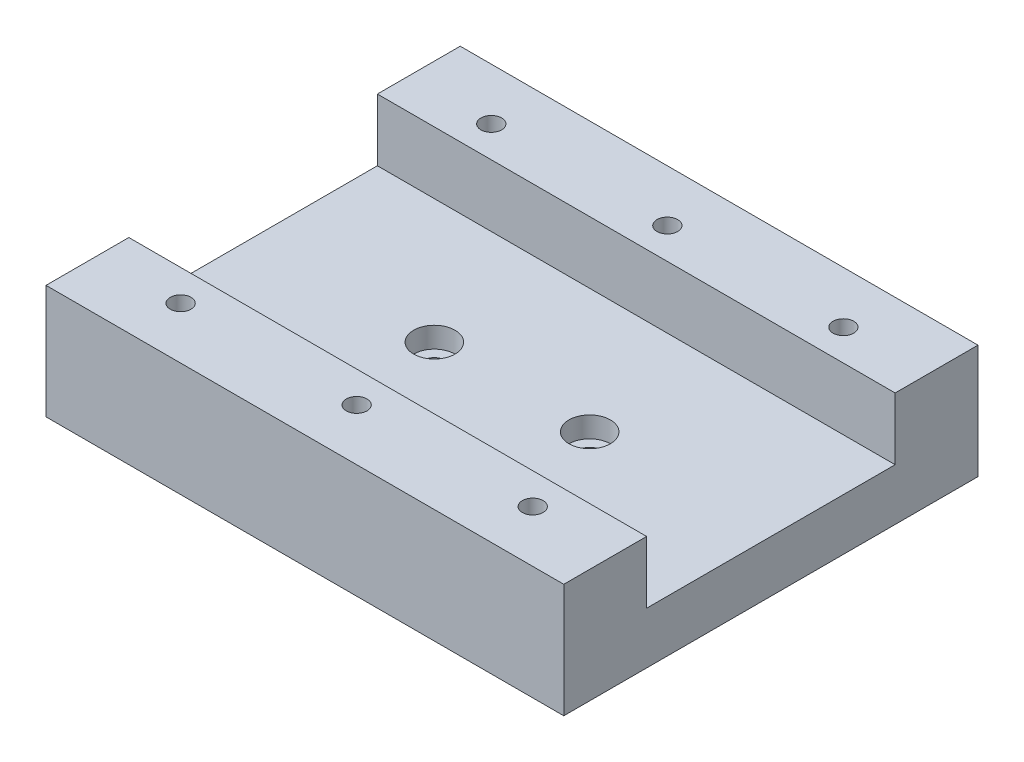
SolidWorks part; units mm, degrees
material "1060 Alloy"
ref_plane "Front Plane" through (0, 0, 0) normal (0, 0, 1) x (1, 0, 0)
ref_plane "Top Plane" through (0, 0, 0) normal (0, 1, 0) x (1, 0, 0)
ref_plane "Right Plane" through (0, 0, 0) normal (1, 0, 0) x (0, 0, -1)
sketch "Sketch1" plane through (0, 0, 0) normal (0, 1, 0) x (1, 0, 0)
  line L1 (-25, 20) -> (25, 20)
  line L2 (-25, 20) -> (-25, -20)
  line L3 (-25, -20) -> (25, -20)
  line L4 (25, 20) -> (25, -20)
  line L5 (-25, 20) -> (25, -20) construction
  line L6 (-25, -20) -> (25, 20) construction
  point P0 (0, 0)
  dimension "D1" = 40
  dimension "D2" = 50
extrude "Boss-Extrude1" add sketch "Sketch1" along normal blind 5
sketch "Sketch2" plane through (0, 5, 0) normal (0, 1, 0) x (1, 0, 0)
  line L0 (-7.5, 0) -> (7.5, 0) construction
  circle A0 centre (-7.5, 0) radius 1
  circle A1 centre (7.5, 0) radius 1
  point P4 (0, 0)
  dimension "D2" = 2
  dimension "D3" = 2
  dimension "D1" = 15
extrude "Cut-Extrude1" cut sketch "Sketch2" against normal through all
sketch "Sketch3" plane through (0, 5, 0) normal (0, 1, 0) x (1, 0, 0)
  circle A0 centre (-7.5, 0) radius 2
  circle A1 centre (7.5, 0) radius 2
  dimension "D1" = 4
  dimension "D2" = 4
extrude "Cut-Extrude2" cut sketch "Sketch3" against normal blind 2
sketch "Sketch5" plane through (0, 5, 0) normal (0, 1, 0) x (1, 0, 0)
  line L0 (25, -20) -> (25, 20) construction
  line L1 (-25, 20) -> (25, 20)
  line L2 (-25, 20) -> (-25, 12)
  line L3 (-25, 12) -> (25, 12)
  line L4 (25, 20) -> (25, 12)
  line L6 (-25, -20) -> (25, -20)
  line L7 (-25, -20) -> (-25, -12)
  line L8 (-25, -12) -> (25, -12)
  line L9 (25, -20) -> (25, -12)
  dimension "D1" = 8
  dimension "D2" = 8
extrude "Boss-Extrude2" add sketch "Sketch5" along normal blind 6
sketch "Sketch4" plane through (0, 5, 0) normal (0, 1, 0) x (1, 0, 0)
  line L0 (0, 20) -> (0, -20) construction
  line L1 (25, 20) -> (-25, 20) construction
  line L2 (-25, -20) -> (25, -20) construction
  circle A0 centre (-17, 15) radius 1
  circle A1 centre (0, 15) radius 1
  circle A2 centre (17, 15) radius 1
  circle A3 centre (-17, -15) radius 1
  circle A4 centre (0, -15) radius 1
  circle A5 centre (17, -15) radius 1
  dimension "D1" = 2
  dimension "D2" = 2
  dimension "D3" = 2
  dimension "D4" = 2
  dimension "D5" = 2
  dimension "D6" = 2
  dimension "D7" = 15
  dimension "D8" = 15
  dimension "D9" = 17
  dimension "D10" = 17
  dimension "D11" = 17
  dimension "D12" = 17
extrude "Cut-Extrude3" cut sketch "Sketch4" against normal through all both and the other way through all
